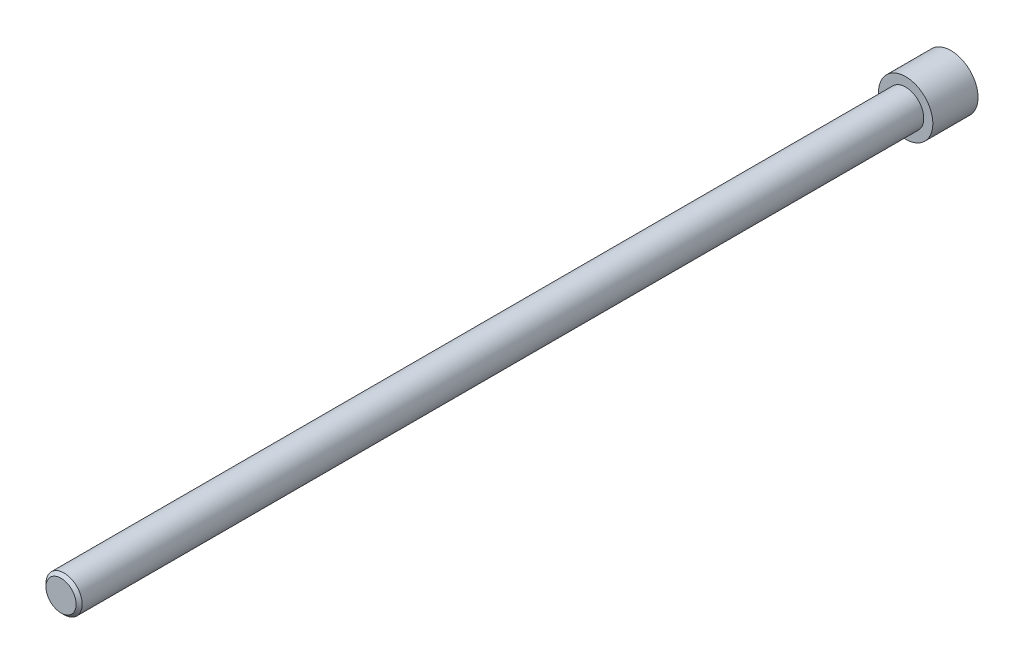
SolidWorks part; units mm, degrees
ref_plane "Přední rovina" through (0, 0, 0) normal (0, 0, 1) x (1, 0, 0)
ref_plane "Horní rovina" through (0, 0, 0) normal (0, 1, 0) x (1, 0, 0)
ref_plane "Pravá rovina" through (0, 0, 0) normal (1, 0, 0) x (0, 0, -1)
sketch "Skica1" plane through (0, 0, 0) normal (0, 0, 1) x (1, 0, 0)
  circle A0 centre (0, 0) radius 3
  dimension "D1" = 6
extrude "Přidat vysunutím1" add sketch "Skica1" along normal blind 140
sketch "Skica2" plane through (0, 0, 0) normal (0, 0, -1) x (-1, 0, 0)
  circle A0 centre (0, 0) radius 4.5
  dimension "D1" = 9
extrude "Přidat vysunutím2" add sketch "Skica2" along normal blind 7.5
sketch "Skica3" plane through (0, 0, -7.5) normal (0, 0, -1) x (-1, 0, 0)
  line L1 (0, -2.7713) -> (2.4, -1.3856)
  line L2 (2.4, -1.3856) -> (2.4, 1.3856)
  line L3 (2.4, 1.3856) -> (0, 2.7713)
  line L4 (0, 2.7713) -> (-2.4, 1.3856)
  line L5 (-2.4, 1.3856) -> (-2.4, -1.3856)
  line L6 (-2.4, -1.3856) -> (0, -2.7713)
  circle A0 centre (0, 0) radius 2.4 construction
  dimension "D1" = 4.8
extrude "Odebrat vysunutím1" cut sketch "Skica3" against normal blind 4.5
chamfer "Zkosení1" distance 0.5 angle 45 1 edges at (3, 0, 140)
